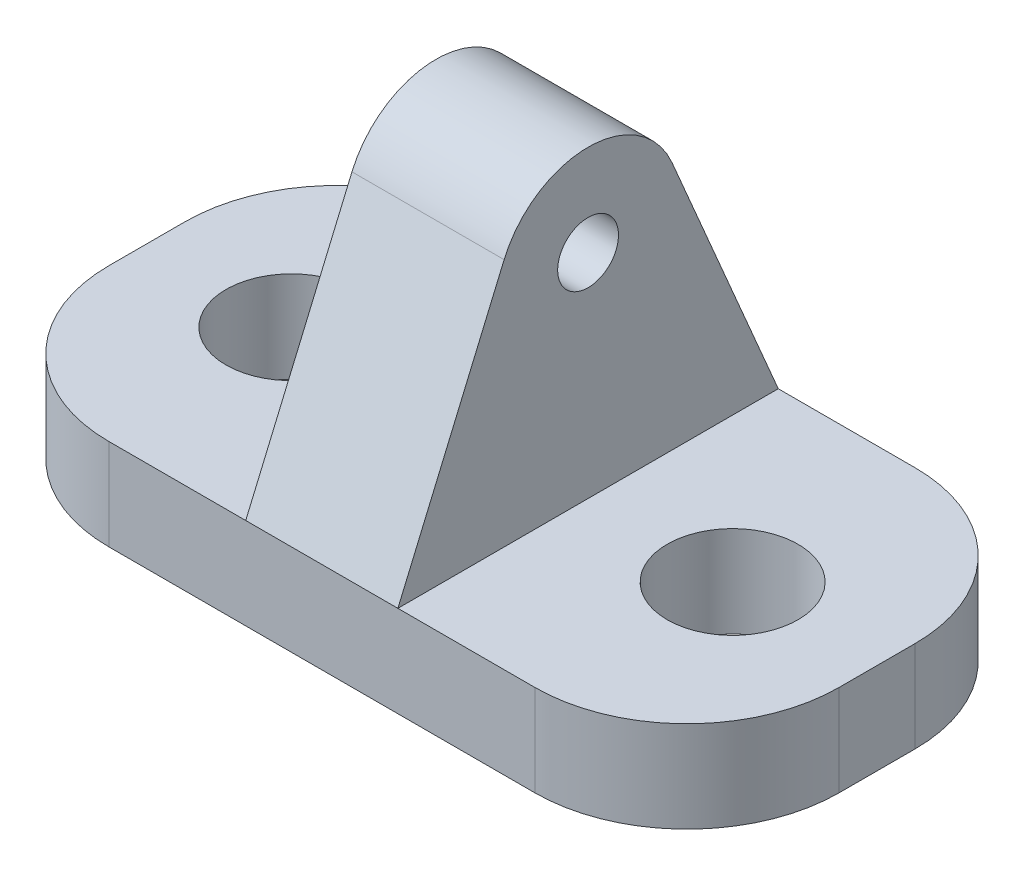
SolidWorks part; units mm, degrees
material "ABS"
ref_plane "Front Plane" through (0, 0, 0) normal (0, 0, 1) x (1, 0, 0)
ref_plane "Top Plane" through (0, 0, 0) normal (0, 1, 0) x (1, 0, 0)
ref_plane "Right Plane" through (0, 0, 0) normal (1, 0, 0) x (0, 0, -1)
sketch "Sketch1" plane through (0, 0, 0) normal (0, 1, 0) x (1, 0, 0)
  line L0 (-7.25, 0) -> (7.25, 0) construction
  line L2 (-2.5, -6.25) -> (2.5, -6.25) construction
  line L3 (-2.5, -6.25) -> (-2.5, 6.25) construction
  line L4 (-2.5, 6.25) -> (2.5, 6.25) construction
  line L5 (2.5, -6.25) -> (2.5, 6.25) construction
  line L6 (-2.5, -6.25) -> (2.5, 6.25) construction
  line L7 (-2.5, 6.25) -> (2.5, -6.25) construction
  line L8 (-7, -6.25) -> (7, -6.25)
  line L9 (-12, -1.25) -> (-12, 1.25)
  line L10 (-7, 6.25) -> (7, 6.25)
  line L11 (12, -1.25) -> (12, 1.25)
  line L12 (-12, -6.25) -> (12, 6.25) construction
  line L13 (-12, 6.25) -> (12, -6.25) construction
  circle A0 centre (-7.25, 0) radius 2.15
  circle A1 centre (7.25, 0) radius 2.15
  circle A2 centre (-7.25, 0) radius 4.75 construction
  circle A3 centre (7.25, 0) radius 4.75 construction
  arc A4 (-7, -6.25) -> (-12, -1.25) centre (-7, -1.25) cw
  arc A5 (7, -6.25) -> (12, -1.25) centre (7, -1.25) ccw
  arc A6 (7, 6.25) -> (12, 1.25) centre (7, 1.25) cw
  arc A7 (-12, 1.25) -> (-7, 6.25) centre (-7, 1.25) cw
  point P4 (0, 0)
  point P9 (0, 0)
  point P14 (0, 0)
  dimension "D1" = 4.3
  dimension "D3" = 9.5
  dimension "D5" = 5
  dimension "D2" = 14.5
  dimension "D4" = 12.5
extrude "Boss-Extrude1" add sketch "Sketch1" along normal mid plane 3
sketch "Sketch3" plane through (0, 0, 6.25) normal (0, 0, 1) x (1, 0, 0)
  line L0 (-7, 1.5) -> (7, 1.5) construction
  line L1 (-2.5, 11.5) -> (2.5, 11.5) construction
  line L2 (-2.5, 11.5) -> (-2.5, 1.5) construction
  line L3 (-2.5, 1.5) -> (2.5, 1.5) construction
  line L4 (2.5, 11.5) -> (2.5, 1.5) construction
  line L5 (-2.5, 11.5) -> (2.5, 1.5) construction
  line L6 (-2.5, 1.5) -> (2.5, 11.5) construction
  line L8 (-12, 1.5) -> (-12, -1.5) construction
  line L9 (-2.5, 1.5) -> (-12, 1.5) construction
  line L10 (-2.5, 11.5) -> (2.5, 11.5)
  line L11 (-4.5, 7) -> (-12, 7) construction
  line L12 (-4.5, 7) -> (-4.5, 11.5) construction
  line L13 (-4.5, 11.5) -> (-12, 11.5) construction
  line L14 (-12, 7) -> (-12, 11.5) construction
  line L15 (-4.5, 7) -> (-12, 11.5) construction
  line L16 (-4.5, 11.5) -> (-12, 7) construction
  line L17 (-2.5, 1.5) -> (-2.5, 11.5)
  line L18 (-2.5, 1.5) -> (-12, 1.5) construction
  line L19 (-2.5, 1.5) -> (-2.5, 6.5) construction
  line L20 (-2.5, 6.5) -> (-12, 6.5) construction
  line L21 (-12, 1.5) -> (-12, 6.5) construction
  line L22 (-2.5, 1.5) -> (-12, 6.5) construction
  line L23 (-2.5, 6.5) -> (-12, 1.5) construction
  line L24 (0, -10) -> (0, 22.0144) construction
  line L25 (2.5, 11.5) -> (2.5, 1.5)
  line L26 (2.5, 1.5) -> (-2.5, 1.5)
  point P0 (0, 6.5)
  point P7 (-8.25, 9.25)
  point P11 (-7.25, 4)
  point P13 (0, 11.5)
  dimension "D1" = 9.5
  dimension "D2" = 10
  dimension "D3" = 7.5
  dimension "D4" = 4.5
  dimension "D5" = 5
extrude "Boss-Extrude3" add sketch "Sketch3" against normal up to surface (12.5 mm away) up to face at (0, 0, -6.25)
sketch "Sketch4" plane through (-2.5, 0, 0) normal (-1, 0, 0) x (0, 0, 1)
  line L0 (-2.7591, 9.6778) -> (-6.25, 1.5)
  line L1 (6.25, 1.5) -> (2.7591, 9.6778)
  line L2 (-6.25, 11.5) -> (6.25, 11.5) construction
  line L3 (-6.25, 1.5) -> (-6.25, 11.5)
  line L4 (-6.25, 11.5) -> (6.25, 11.5)
  line L5 (6.25, 11.5) -> (6.25, 1.5)
  circle A0 centre (0, 8.5) radius 1
  arc A1 (2.7591, 9.6778) -> (-2.7591, 9.6778) centre (0, 8.5) ccw
  circle A3 centre (0, 8.5) radius 3 construction
  point P9 (2.8689, 19.3771)
  line M5 (-6.25, 11.5) -> (-6.25, 1.5)
  line M7 (6.25, 1.5) -> (6.25, 11.5)
  line M8 (6.25, 11.5) -> (-6.25, 11.5)
  dimension "D1" = 2
  dimension "D2" = 2
extrude "Cut-Extrude1" cut sketch "Sketch4" against normal through all both and the other way through all contours A1 L4 L0 M5 | A1 L1 M7 M8 | A0
